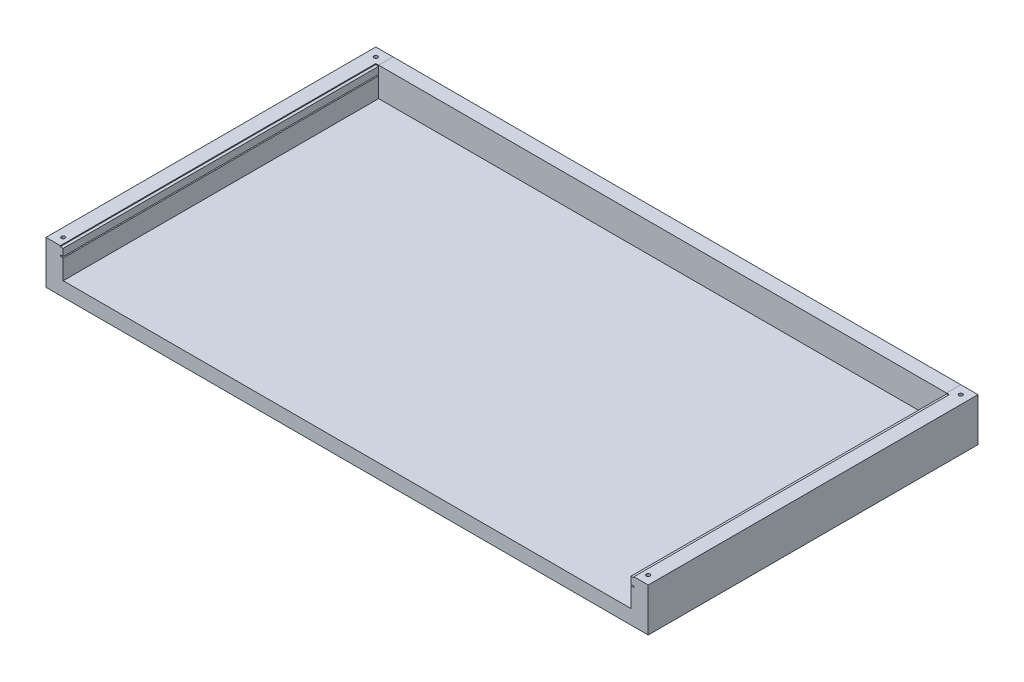
SolidWorks part; units mm, degrees
ref_plane "Front Plane" through (0, 0, 0) normal (0, 0, 1) x (1, 0, 0)
ref_plane "Top Plane" through (0, 0, 0) normal (0, 1, 0) x (1, 0, 0)
ref_plane "Right Plane" through (0, 0, 0) normal (1, 0, 0) x (0, 0, -1)
sketch "Sketch3" plane through (0, 0, 0) normal (0, 0, 1) x (1, 0, 0)
  line L1 (-990, 50) -> (990, 50)
  line L3 (-1050, 0) -> (1050, 0)
  line L5 (-1050, 151.05) -> (-990, 151.05)
  line L6 (-990, 151.05) -> (-990, 50)
  line L7 (0, 0) -> (0, 50) construction
  line L8 (990, 151.05) -> (990, 50)
  line L9 (1050, 151.05) -> (990, 151.05)
  line L11 (1050, 151.05) -> (1050, 0)
  line L12 (-1050, 151.05) -> (-1050, 0)
  dimension "D1" = 2100
  dimension "D3" = 60
  dimension "D4" = 101.05
  dimension "D5" = 50
extrude "Boss-Extrude1" add sketch "Sketch3" along normal blind 1150
sketch "Sketch4" plane through (0, 0, 0) normal (0, 1, 0) x (1, 0, 0)
  line L0 (-990, 0) -> (-990, -50)
  line L1 (-990, -1150) -> (-990, 0) construction
  line L2 (-990, -50) -> (990, -50)
  line L3 (990, -1150) -> (990, 0) construction
  line L4 (990, -50) -> (990, 0)
  line L5 (990, 0) -> (-990, 0)
  dimension "D1" = 50
extrude "Boss-Extrude2" add sketch "Sketch4" along normal up to surface (151.05 mm away) separate body up to face at (-1020, 151.05, 575)
sketch "Sketch6" plane through (0, 0, 0) normal (0, 0, 1) x (1, 0, 0)
  line L0 (1000, 151.05) -> (-1000, 151.05)
  line L1 (-990, 151.05) -> (-990, 0) construction
  line L2 (-1000, 151.05) -> (-1000, 147.85)
  line L3 (-1000, 147.85) -> (1000, 147.85)
  line L4 (1000, 147.85) -> (1000, 151.05)
  line L7 (-1000, 123.05) -> (1000, 123.05)
  line L8 (1000, 123.05) -> (1000, 118.85)
  line L9 (1000, 118.85) -> (-1000, 118.85)
  line L10 (-1000, 118.85) -> (-1000, 123.05)
  line L11 (990, 151.05) -> (-990, 151.05) construction
  dimension "D1" = 3.2
  dimension "D2" = 10
  dimension "D3" = 10
  dimension "D4" = 28
  dimension "D5" = 4.2
extrude "Cut-Extrude2" cut sketch "Sketch6" against normal up to surface (1100 mm away) from surface at 1150 up to face at (0, 75.525, 50) starting at face at (0, 88.025, 1150)
sketch "Sketch7" plane through (0, 0, 0) normal (0, 1, 0) x (1, 0, 0)
  line L0 (1050, -1150) -> (1050, 0) construction
  line L1 (0, -1150) -> (0, 0) construction
  line L2 (990, -1150) -> (-990, -1150) construction
  line L3 (1050, -575) -> (-1050, -575) construction
  line L4 (1050, -1150) -> (1050, 0) construction
  line L5 (-1050, -1150) -> (-1050, 0) construction
  line L6 (1050, 0) -> (990, 0) construction
  circle A0 centre (1020, -30) radius 6.35
  circle A2 centre (-1020, -30) radius 6.35
  circle A3 centre (-1020, -1120) radius 6.35
  circle A4 centre (1020, -1120) radius 6.35
  point P0 (0, 0)
  point P26 (0, 0)
  dimension "D1" = 12.7
  dimension "D2" = 30
  dimension "D3" = 30
extrude "Cut-Extrude3" cut sketch "Sketch7" against normal through all from surface at 151.05 starting at face at (1013.3333, 151.05, 400)
